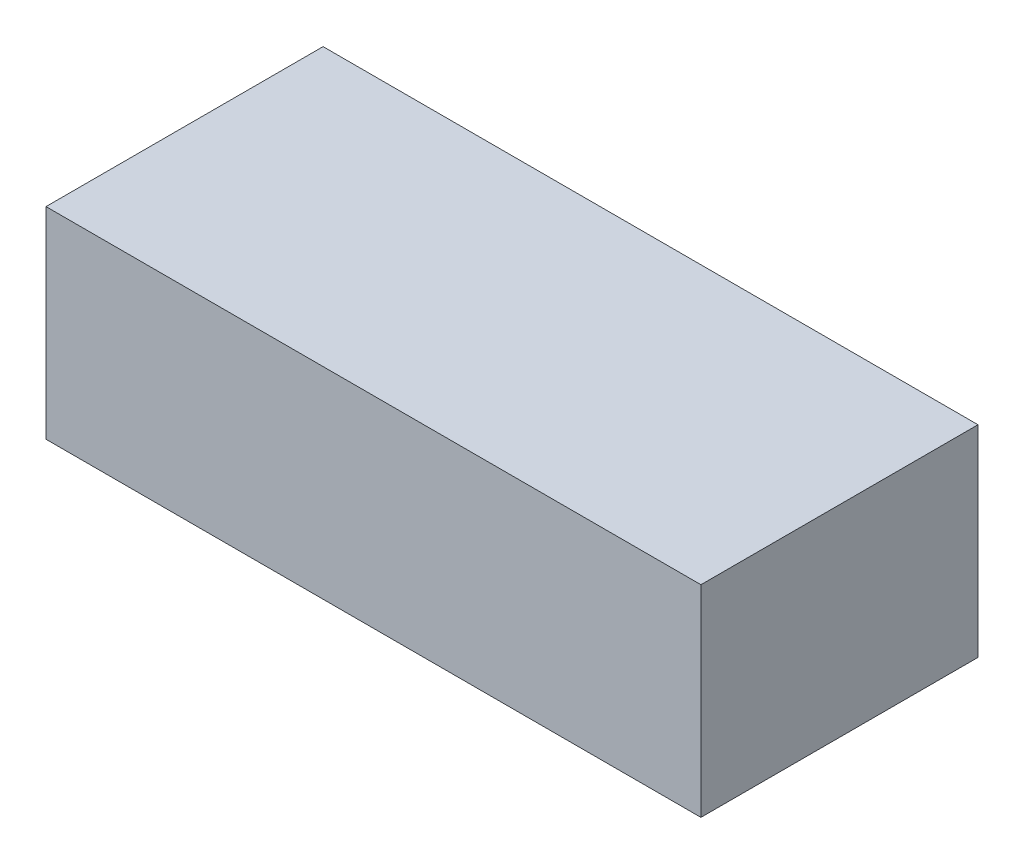
SolidWorks part; units mm, degrees
ref_plane "Front Plane" through (0, 0, 0) normal (0, 0, 1) x (1, 0, 0)
ref_plane "Top Plane" through (0, 0, 0) normal (0, 1, 0) x (1, 0, 0)
ref_plane "Right Plane" through (0, 0, 0) normal (1, 0, 0) x (0, 0, -1)
sketch "Sketch1" plane through (0, 0, 0) normal (0, 1, 0) x (1, 0, 0)
  line L1 (0, 0) -> (78, 0)
  line L2 (0, 0) -> (0, 33)
  line L3 (0, 33) -> (78, 33)
  line L4 (78, 0) -> (78, 33)
  dimension "D1" = 78
  dimension "D2" = 33
extrude "Boss-Extrude1" add sketch "Sketch1" along normal blind 24
